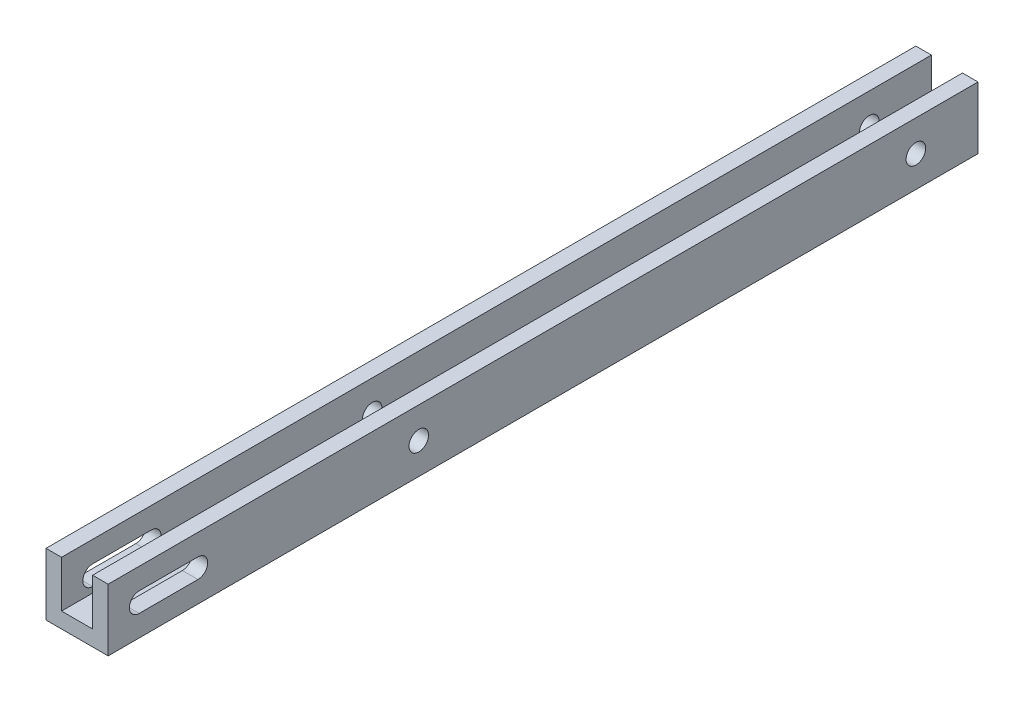
SolidWorks part; units mm, degrees
ref_plane "Front" through (0, 0, 0) normal (0, 0, 1) x (1, 0, 0)
ref_plane "Top" through (0, 0, 0) normal (0, 1, 0) x (1, 0, 0)
ref_plane "Right" through (0, 0, 0) normal (1, 0, 0) x (0, 0, -1)
sketch "Sketch1" plane through (0, 0, 0) normal (0, 0, 1) x (1, 0, 0)
  line L0 (0, -6.35) -> (0, 6.35) construction
  line L1 (-6.35, 0) -> (6.35, 0) construction
  line L2 (3.175, 6.35) -> (-3.175, 6.35) construction
  line L3 (-6.35, -6.35) -> (6.35, -6.35)
  line L4 (-6.35, -6.35) -> (-6.35, 6.35)
  line L5 (-6.35, 6.35) -> (6.35, 6.35)
  line L6 (6.35, -6.35) -> (6.35, 6.35)
  line L7 (-6.35, -6.35) -> (6.35, 6.35) construction
  line L8 (-6.35, 6.35) -> (6.35, -6.35) construction
  point P3 (0, 0)
  point P4 (0, 0)
  point P8 (0, 0)
  point P13 (6.35, -3.175)
  point P17 (0, 6.35)
  dimension "Outside Width" = 12.7
  dimension "Outside Height" = 12.7
  dimension "Wall Thickness" = 3.175
  dimension "Inside Height" = 9.525
sketch "Sketch2" plane through (0, 0, 0) normal (0, 0, 1) x (1, 0, 0)
  line L0 (-6.35, 6.35) -> (-6.35, -6.35)
  line L1 (-6.35, -6.35) -> (6.35, -6.35)
  line L2 (6.35, -6.35) -> (6.35, 6.35)
  line L3 (-6.35, 6.35) -> (-3.175, 6.35)
  line L4 (-3.175, 6.35) -> (-3.175, -3.175)
  line L5 (-3.175, -3.175) -> (3.175, -3.175)
  line L6 (3.175, -3.175) -> (3.175, 6.35)
  line L7 (3.175, 6.35) -> (6.35, 6.35)
  point P2 (0, -6.35)
extrude "Boss-Extrude1" add sketch "Sketch2" along normal mid plane 177.8
sketch "Profile" plane through (0, 0, 0) normal (0, 0, 1) x (1, 0, 0)
  line L0 (-6.35, 0) -> (6.35, 0) construction
  line L1 (6.35, 0) -> (6.35, 6.35) construction
  line L2 (6.35, 6.35) -> (3.175, 6.35) construction
  line L3 (6.35, -6.35) -> (6.35, 6.35) construction
  line L4 (3.175, 6.35) -> (3.175, -3.175) construction
  line L5 (6.35, 6.35) -> (3.175, 6.35) construction
  point P14 (0, 0)
  dimension "Width" = 12.7
  dimension "Height" = 6.35
  dimension "Thickness" = 3.175
sketch "Length" plane through (0, 0, 0) normal (1, 0, 0) x (0, 0, -1)
  line L0 (-88.9, -6.35) -> (88.9, -6.35) construction
  line L1 (88.9, -6.35) -> (88.9, 6.35) construction
  line L2 (-88.9, -6.35) -> (-88.9, 6.35) construction
  line L3 (-88.9, -6.35) -> (88.9, -6.35) construction
  dimension "Length" = 177.8
sketch "Break Positions" plane through (0, 0, 0) normal (1, 0, 0) x (0, 0, -1)
  line L3 (-88.9, -6.35) -> (-88.9, 6.35) construction
  line L4 (-88.9, -6.35) -> (88.9, -6.35) construction
  line L5 (88.9, 6.35) -> (88.9, -6.35) construction
  line L6 (-88.9, -6.35) -> (88.9, -6.35) construction
  point P0 (-59.7398, -6.35)
  point P1 (59.7398, -6.35)
  dimension "D1" = 29.1602
  dimension "D2" = 29.1602
sketch "Sketch3" plane through (6.35, 0, 0) normal (1, 0, 0) x (0, 0, -1)
  line L0 (-88.9, 0) -> (88.9, 0) construction
  line L1 (-88.9, -6.35) -> (-88.9, 6.35) construction
  line L2 (88.9, -6.35) -> (88.9, 6.35) construction
  line L3 (-82.55, 0) -> (-70.55, 0) construction
  line L4 (-82.55, 2) -> (-70.55, 2)
  line L5 (-82.55, -2) -> (-70.55, -2)
  circle A0 centre (-25.4, 0) radius 2
  circle A1 centre (76.2, 0) radius 2
  arc A2 (-82.55, 2) -> (-82.55, -2) centre (-82.55, 0) ccw
  arc A3 (-70.55, -2) -> (-70.55, 2) centre (-70.55, 0) ccw
  point P12 (-76.55, 0)
  dimension "D1" = 2
  dimension "D2" = 4
  dimension "D3" = 4
  dimension "D4" = 12
  dimension "D5" = 6.35
  dimension "D6" = 114.3
  dimension "D7" = 12.7
extrude "Cut-Extrude1" cut sketch "Sketch3" against normal through all both and the other way through all
